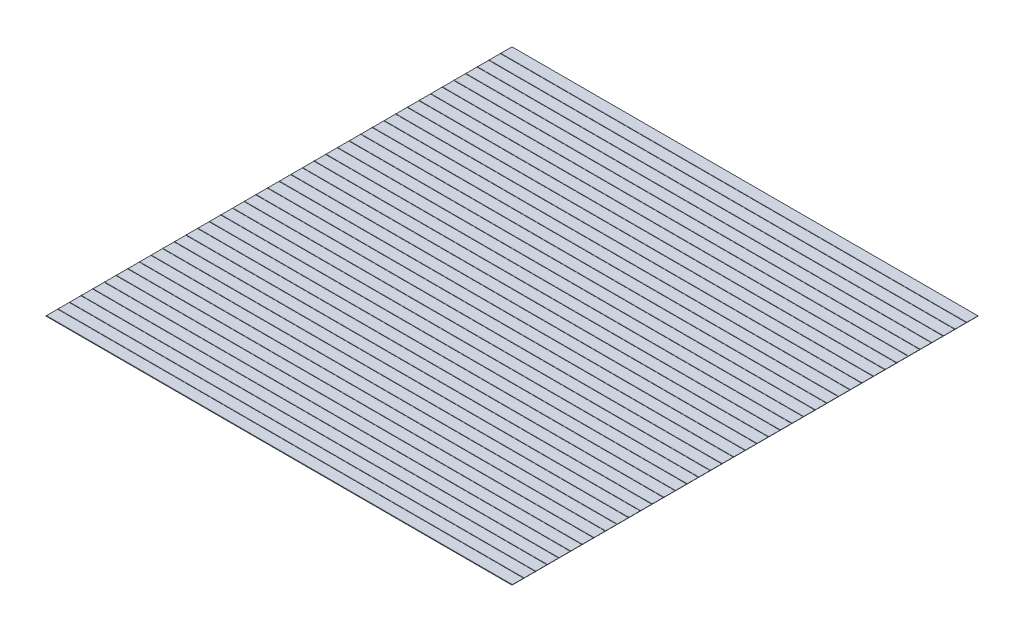
SolidWorks part; units mm, degrees
ref_plane "前视基准面" through (0, 0, 0) normal (0, 0, 1) x (1, 0, 0)
ref_plane "上视基准面" through (0, 0, 0) normal (0, 1, 0) x (1, 0, 0)
ref_plane "右视基准面" through (0, 0, 0) normal (1, 0, 0) x (0, 0, -1)
sketch "草图1" plane through (0, 0, 0) normal (1, 0, 0) x (0, 0, -1)
  line L0 (0, 0) -> (10, 0)
  line L1 (10, 0) -> (10, -5)
  line L2 (10, -5) -> (250, -5)
  line L3 (250, -5) -> (250, 0)
  line L4 (250, 0) -> (260, 0)
  line L5 (260, 0) -> (260, -5)
  line L6 (260, -5) -> (500, -5)
  line L7 (500, -5) -> (500, 0)
  line L8 (500, 0) -> (510, 0)
  line L9 (510, 0) -> (510, -5)
  line L10 (510, -5) -> (750, -5)
  line L11 (750, -5) -> (750, 0)
  line L12 (750, 0) -> (760, 0)
  line L13 (760, 0) -> (760, -5)
  line L14 (760, -5) -> (1000, -5)
  line L15 (1000, -5) -> (1000, 0)
  line L16 (1000, 0) -> (1010, 0)
  line L17 (1010, 0) -> (1010, -5)
  line L18 (1010, -5) -> (1250, -5)
  line L19 (1250, -5) -> (1250, 0)
  line L20 (1250, 0) -> (1260, 0)
  line L21 (1260, 0) -> (1260, -5)
  line L22 (1260, -5) -> (1500, -5)
  line L23 (1500, -5) -> (1500, 0)
  line L24 (1500, 0) -> (1510, 0)
  line L25 (1510, 0) -> (1510, -5)
  line L26 (1510, -5) -> (1750, -5)
  line L27 (1750, -5) -> (1750, 0)
  line L28 (1750, 0) -> (1760, 0)
  line L29 (1760, 0) -> (1760, -5)
  line L30 (1760, -5) -> (2000, -5)
  line L31 (2000, -5) -> (2000, 0)
  line L32 (2000, 0) -> (2010, 0)
  line L33 (2010, 0) -> (2010, -5)
  line L34 (2010, -5) -> (2250, -5)
  line L35 (2250, -5) -> (2250, 0)
  line L36 (2250, 0) -> (2260, 0)
  line L37 (2260, 0) -> (2260, -5)
  line L38 (2260, -5) -> (2500, -5)
  line L39 (2500, -5) -> (2500, 0)
  line L40 (2500, 0) -> (2510, 0)
  line L41 (2510, 0) -> (2510, -5)
  line L42 (2510, -5) -> (2750, -5)
  line L43 (2750, -5) -> (2750, 0)
  line L44 (2750, 0) -> (2760, 0)
  line L45 (2760, 0) -> (2760, -5)
  line L46 (2760, -5) -> (3000, -5)
  line L47 (3000, -5) -> (3000, 0)
  line L48 (3000, 0) -> (3010, 0)
  line L49 (3010, 0) -> (3010, -5)
  line L50 (3010, -5) -> (3250, -5)
  line L51 (3250, -5) -> (3250, 0)
  line L52 (3250, 0) -> (3260, 0)
  line L53 (3260, 0) -> (3260, -5)
  line L54 (3260, -5) -> (3500, -5)
  line L55 (3500, -5) -> (3500, 0)
  line L56 (3500, 0) -> (3510, 0)
  line L57 (3510, 0) -> (3510, -5)
  line L58 (3510, -5) -> (3750, -5)
  line L59 (3750, -5) -> (3750, 0)
  line L60 (3750, 0) -> (3760, 0)
  line L61 (3760, 0) -> (3760, -5)
  line L62 (3760, -5) -> (4000, -5)
  line L63 (4000, -5) -> (4000, 0)
  line L64 (4000, 0) -> (4010, 0)
  line L65 (4010, 0) -> (4010, -5)
  line L66 (4010, -5) -> (4250, -5)
  line L67 (4250, -5) -> (4250, 0)
  line L68 (4250, 0) -> (4260, 0)
  line L69 (4260, 0) -> (4260, -5)
  line L70 (4260, -5) -> (4500, -5)
  line L71 (4500, -5) -> (4500, 0)
  line L72 (4500, 0) -> (4510, 0)
  line L73 (4510, 0) -> (4510, -5)
  line L74 (4510, -5) -> (4750, -5)
  line L75 (4750, -5) -> (4750, 0)
  line L76 (4750, 0) -> (4760, 0)
  line L77 (4760, 0) -> (4760, -5)
  line L78 (4760, -5) -> (5000, -5)
  line L79 (5000, -5) -> (5000, 0)
  line L80 (5000, 0) -> (5010, 0)
  line L81 (5010, 0) -> (5010, -5)
  line L82 (5010, -5) -> (5250, -5)
  line L83 (5250, -5) -> (5250, 0)
  line L84 (5250, 0) -> (5260, 0)
  line L85 (5260, 0) -> (5260, -5)
  line L86 (5260, -5) -> (5500, -5)
  line L87 (5500, -5) -> (5500, 0)
  line L88 (5500, 0) -> (5510, 0)
  line L89 (5510, 0) -> (5510, -5)
  line L90 (5510, -5) -> (5750, -5)
  line L91 (5750, -5) -> (5750, 0)
  line L92 (5750, 0) -> (5760, 0)
  line L93 (5760, 0) -> (5760, -5)
  line L94 (5760, -5) -> (6000, -5)
  line L95 (6000, -5) -> (6000, 0)
  line L96 (6000, 0) -> (6010, 0)
  line L97 (6010, 0) -> (6010, -5)
  line L98 (6010, -5) -> (6250, -5)
  line L99 (6250, -5) -> (6250, 0)
  line L100 (6250, 0) -> (6260, 0)
  line L101 (6260, 0) -> (6260, -5)
  line L102 (6260, -5) -> (6500, -5)
  line L103 (6500, -5) -> (6500, 0)
  line L104 (6500, 0) -> (6510, 0)
  line L105 (6510, 0) -> (6510, -5)
  line L106 (6510, -5) -> (6750, -5)
  line L107 (6750, -5) -> (6750, 0)
  line L108 (6750, 0) -> (6760, 0)
  line L109 (6760, 0) -> (6760, -5)
  line L110 (6760, -5) -> (7000, -5)
  line L111 (7000, -5) -> (7000, 0)
  line L112 (7000, 0) -> (7010, 0)
  line L113 (7010, 0) -> (7010, -5)
  line L114 (7010, -5) -> (7250, -5)
  line L115 (7250, -5) -> (7250, 0)
  line L116 (7250, 0) -> (7260, 0)
  line L117 (7260, 0) -> (7260, -5)
  line L118 (7260, -5) -> (7500, -5)
  line L119 (7500, -5) -> (7500, 0)
  line L120 (7500, 0) -> (7510, 0)
  line L121 (7510, 0) -> (7510, -5)
  line L122 (7510, -5) -> (7750, -5)
  line L123 (7750, -5) -> (7750, 0)
  line L124 (7750, 0) -> (7760, 0)
  line L125 (7760, 0) -> (7760, -5)
  line L126 (7760, -5) -> (8000, -5)
  line L127 (8000, -5) -> (8000, 0)
  line L128 (8000, 0) -> (8010, 0)
  line L129 (8010, 0) -> (8010, -5)
  line L130 (8010, -5) -> (8250, -5)
  line L131 (8250, -5) -> (8250, 0)
  line L132 (8250, 0) -> (8260, 0)
  line L133 (8260, 0) -> (8260, -5)
  line L134 (8260, -5) -> (8500, -5)
  line L135 (8500, -5) -> (8500, 0)
  line L136 (8500, 0) -> (8510, 0)
  line L137 (8510, 0) -> (8510, -5)
  line L138 (8510, -5) -> (8750, -5)
  line L139 (8750, -5) -> (8750, 0)
  line L140 (8750, 0) -> (8760, 0)
  line L141 (8760, 0) -> (8760, -5)
  line L142 (8760, -5) -> (9000, -5)
  line L143 (9000, -5) -> (9000, 0)
  line L144 (9000, 0) -> (9010, 0)
  line L145 (9010, 0) -> (9010, -5)
  line L146 (9010, -5) -> (9250, -5)
  line L147 (9250, -5) -> (9250, 0)
  line L148 (9250, 0) -> (9260, 0)
  line L149 (9260, 0) -> (9260, -5)
  line L150 (9260, -5) -> (9500, -5)
  line L151 (9500, -5) -> (9500, 0)
  line L152 (9500, 0) -> (9510, 0)
  line L153 (9510, 0) -> (9510, -5)
  line L154 (9510, -5) -> (9750, -5)
  line L155 (9750, -5) -> (9750, 0)
  line L156 (9750, 0) -> (9760, 0)
  line L157 (9760, 0) -> (9760, -5)
  line L158 (9760, -5) -> (10000, -5)
  line L160 (0, 0) -> (0, -10)
  line L161 (0, -10) -> (10000, -10)
  line L162 (10000, -5) -> (10000, -10)
  line L164 (10000, -5) -> (10000, 0) [skipped]
  dimension "D1" = 40
extrude "凸台-拉伸1" add sketch "草图1" along normal blind 10000
